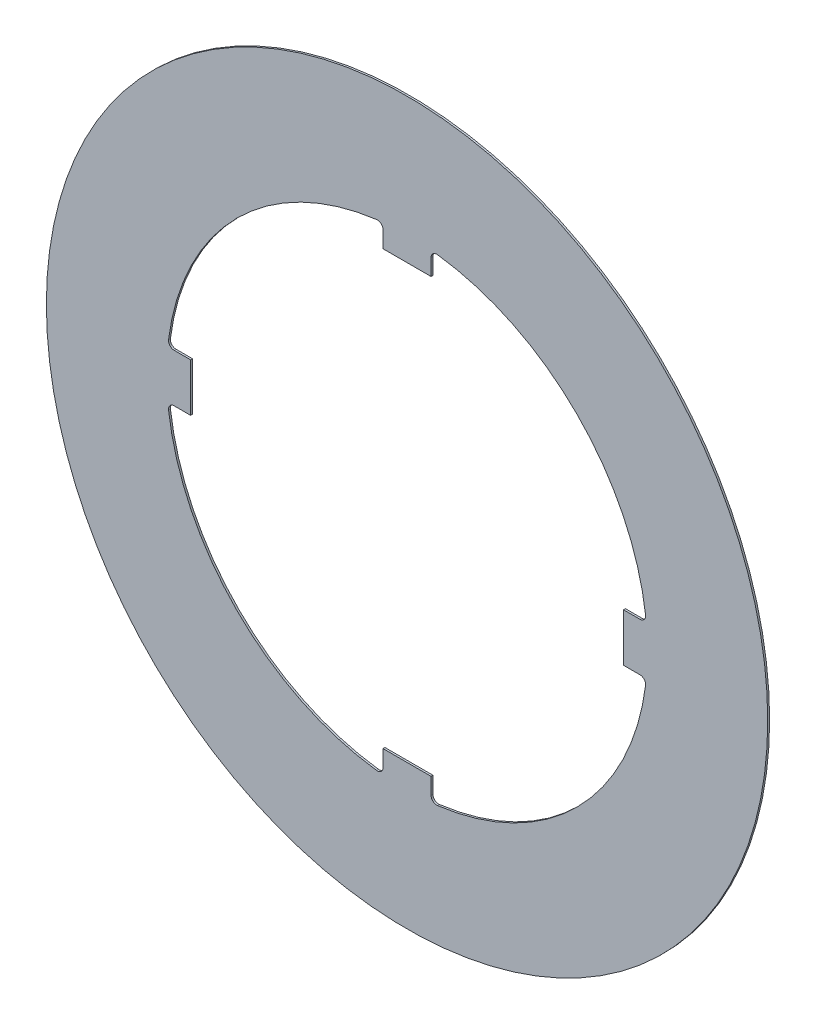
SolidWorks part; units mm, degrees
ref_plane "Front Plane" through (0, 0, 0) normal (0, 0, 1) x (1, 0, 0)
ref_plane "Top Plane" through (0, 0, 0) normal (0, 1, 0) x (1, 0, 0)
ref_plane "Right Plane" through (0, 0, 0) normal (1, 0, 0) x (0, 0, -1)
sketch "Sketch1" plane through (0, 0, 0) normal (0, 0, 1) x (1, 0, 0)
  line L0 (1143, 127) -> (1230.0207, 127)
  line L1 (1143, -127) -> (1230.0207, -127)
  line L2 (1143, 127) -> (1143, -127)
  line L3 (0, 0) -> (555.1928, 0) construction
  line L4 (127, -1143) -> (127, -1230.0207)
  line L5 (127, -1143) -> (-127, -1143)
  line L6 (-127, -1143) -> (-127, -1230.0207)
  line L7 (-1143, -127) -> (-1230.0207, -127)
  line L8 (-1143, -127) -> (-1143, 127)
  line L9 (-1143, 127) -> (-1230.0207, 127)
  line L10 (-127, 1143) -> (-127, 1230.0207)
  line L11 (-127, 1143) -> (127, 1143)
  line L12 (127, 1143) -> (127, 1230.0207)
  arc A0 (1259.7793, 160.7984) -> (160.7984, 1259.7793) centre (0, 0) ccw
  circle A1 centre (0, 0) radius 1905
  arc A2 (1259.7793, 160.7984) -> (1230.0207, 127) centre (1230.0207, 157) cw
  arc A3 (1259.7793, -160.7984) -> (1230.0207, -127) centre (1230.0207, -157) ccw
  arc A4 (160.7984, -1259.7793) -> (127, -1230.0207) centre (157, -1230.0207) cw
  arc A5 (1259.7793, 160.7984) -> (160.7984, 1259.7793) centre (0, 0) ccw
  arc A6 (-160.7984, -1259.7793) -> (-127, -1230.0207) centre (-157, -1230.0207) ccw
  arc A7 (-1259.7793, -160.7984) -> (-1230.0207, -127) centre (-1230.0207, -157) cw
  arc A8 (1259.7793, 160.7984) -> (160.7984, 1259.7793) centre (0, 0) ccw
  arc A9 (-1259.7793, 160.7984) -> (-1230.0207, 127) centre (-1230.0207, 157) ccw
  arc A10 (-160.7984, 1259.7793) -> (-127, 1230.0207) centre (-157, 1230.0207) cw
  arc A11 (-160.7984, 1259.7793) -> (-1259.7793, 160.7984) centre (0, 0) ccw
  arc A12 (160.7984, 1259.7793) -> (127, 1230.0207) centre (157, 1230.0207) ccw
  arc A13 (-160.7984, 1259.7793) -> (-1259.7793, 160.7984) centre (0, 0) ccw
  arc A14 (-160.7984, 1259.7793) -> (-1259.7793, 160.7984) centre (0, 0) ccw
  arc A15 (-160.7984, 1259.7793) -> (-1259.7793, 160.7984) centre (0, 0) ccw
  arc A16 (-1259.7793, -160.7984) -> (-160.7984, -1259.7793) centre (0, 0) ccw
  arc A17 (-1259.7793, -160.7984) -> (-160.7984, -1259.7793) centre (0, 0) ccw
  arc A18 (-1259.7793, -160.7984) -> (-160.7984, -1259.7793) centre (0, 0) ccw
  arc A19 (-1259.7793, -160.7984) -> (-160.7984, -1259.7793) centre (0, 0) ccw
  arc A20 (160.7984, -1259.7793) -> (1259.7793, -160.7984) centre (0, 0) ccw
  arc A21 (160.7984, -1259.7793) -> (1259.7793, -160.7984) centre (0, 0) ccw
  arc A22 (160.7984, -1259.7793) -> (1259.7793, -160.7984) centre (0, 0) ccw
  arc A23 (160.7984, -1259.7793) -> (1259.7793, -160.7984) centre (0, 0) ccw
  arc A24 (1259.7793, 160.7984) -> (160.7984, 1259.7793) centre (0, 0) ccw
  point P1 (0, 0)
  point P5 (127, 1230.0207)
  point P14 (127, 1230.0207)
  point P15 (0, 0)
  point P43 (0, 0)
  dimension "D1" = 2540
  dimension "D2" = 3810
  dimension "D6" = 30
  dimension "D3" = 127
  dimension "D4" = 127
  dimension "D5" = 1143
  dimension "D7" = 4
extrude "Boss-Extrude1" add sketch "Sketch1" along normal mid plane 10 contours A1 A20 A4 L4 L5 L6 A6 A16 A7 L7 L8 L9 A9 A11 A10 L10 L11 L12 A12 A0 A2 L0 L2 L1 A3
